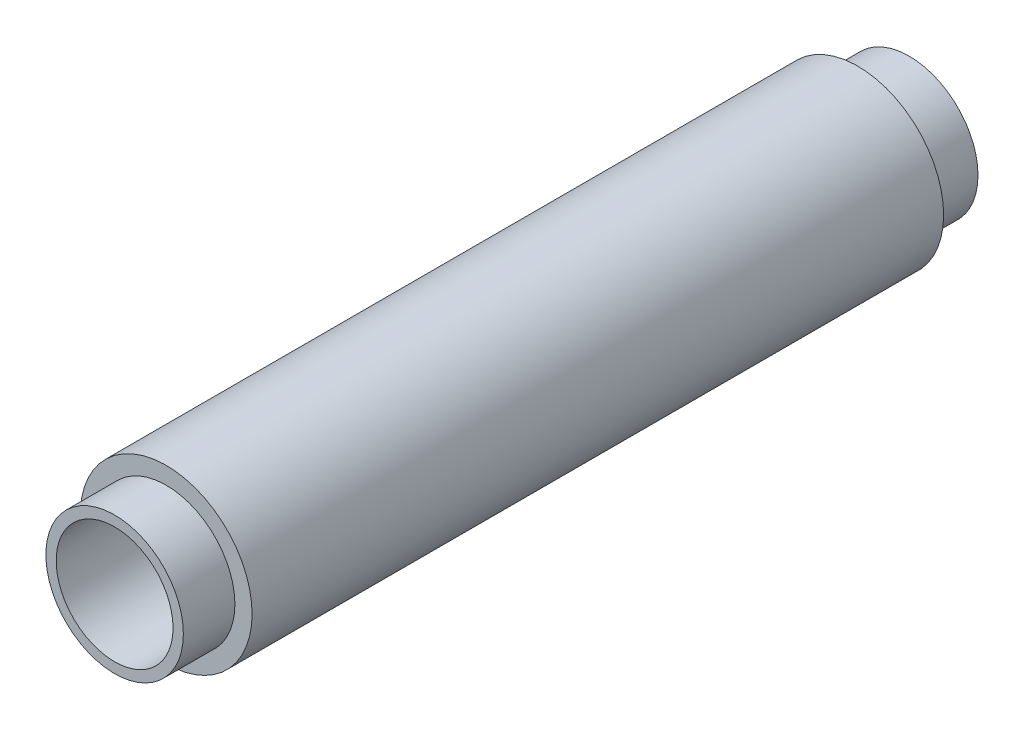
SolidWorks part; units mm, degrees
material "СТ3КП"
ref_plane "Спереди" through (0, 0, 0) normal (0, 0, 1) x (1, 0, 0)
ref_plane "Сверху" through (0, 0, 0) normal (0, 1, 0) x (1, 0, 0)
ref_plane "Справа" through (0, 0, 0) normal (1, 0, 0) x (0, 0, -1)
sketch "Эскиз1" plane through (0, 0, 0) normal (0, 1, 0) x (1, 0, 0)
  line L0 (-1000, 0) -> (49000, 0) construction
  line L1 (0, -1000) -> (0, 49000) construction
  line L3 (-25, 0) -> (-17, 0)
  line L4 (-25, 0) -> (-25, -100.6)
  line L5 (-20, -115.6) -> (-17, -115.6)
  line L6 (-17, 0) -> (-17, -115.6)
  line L7 (-21.5, -115.6) -> (21.5, -115.6) construction
  line L8 (21.5, -100.6) -> (-21.5, -100.6) construction
  line L9 (-20, -100.6) -> (-25, -100.6)
  line L10 (-20, -100.6) -> (-20, -115.6)
  line L13 (-20, -102.1) -> (-20, -114.1) construction
  dimension "D1" = 34
  dimension "D2" = 50
revolve "Повернуть1" add sketch "Эскиз1" angle 360 about L1
mirror "Зеркальное отражение1" about plane through (-25, 0, 0) normal (0, 0, 1) of "Повернуть1"
